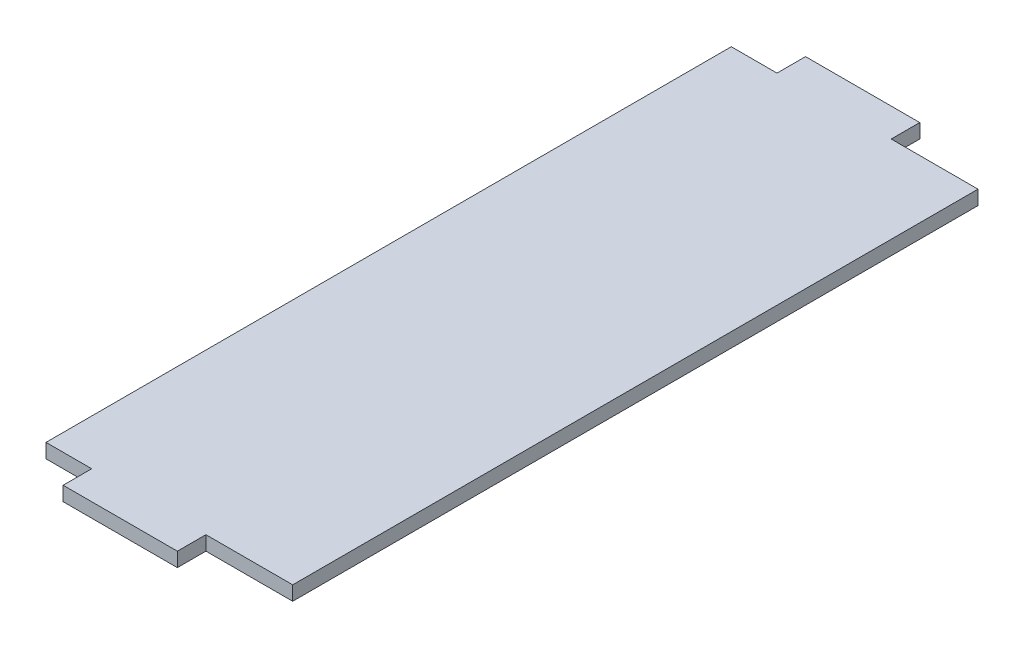
SolidWorks part; units mm, degrees
ref_plane "Front Plane" through (0, 0, 0) normal (0, 0, 1) x (1, 0, 0)
ref_plane "Top Plane" through (0, 0, 0) normal (0, 1, 0) x (1, 0, 0)
ref_plane "Right Plane" through (0, 0, 0) normal (1, 0, 0) x (0, 0, -1)
sketch "Sketch1" plane through (0, 0, 0) normal (0, 1, 0) x (1, 0, 0)
  line L1 (0, 0) -> (5.08, 0)
  line L2 (0, 0) -> (0, 76.2)
  line L3 (0, 76.2) -> (5.08, 76.2)
  line L4 (5.08, 0) -> (5.08, 76.2)
  line L5 (5.08, 0) -> (17.78, 0)
  line L6 (5.08, 0) -> (5.08, 76.2)
  line L7 (5.08, 76.2) -> (17.78, 76.2)
  line L8 (17.78, 0) -> (17.78, 76.2)
  line L9 (17.78, 76.2) -> (27.432, 76.2)
  line L10 (17.78, 76.2) -> (17.78, 0)
  line L11 (17.78, 0) -> (27.432, 0)
  line L12 (27.432, 76.2) -> (27.432, 0)
  line L13 (5.08, 0) -> (17.78, 0)
  line L14 (5.08, 0) -> (5.08, -3.175)
  line L15 (5.08, -3.175) -> (17.78, -3.175)
  line L16 (17.78, 0) -> (17.78, -3.175)
  line L17 (5.08, 76.2) -> (17.78, 76.2)
  line L18 (5.08, 76.2) -> (5.08, 79.375)
  line L19 (5.08, 79.375) -> (17.78, 79.375)
  line L20 (17.78, 76.2) -> (17.78, 79.375)
  dimension "D1" = 76.2
  dimension "D2" = 5.08
  dimension "D3" = 12.7
  dimension "D4" = 9.652
  dimension "D5" = 3.175
  dimension "D6" = 3.175
extrude "Boss-Extrude1" add sketch "Sketch1" along normal blind 1.5875 contours L5 L8 L7 L4 | L1 L4 L3 L2 | L12 L9 L8 L11 | L16 L5 L14 L15 | L7 L20 L19 L18
